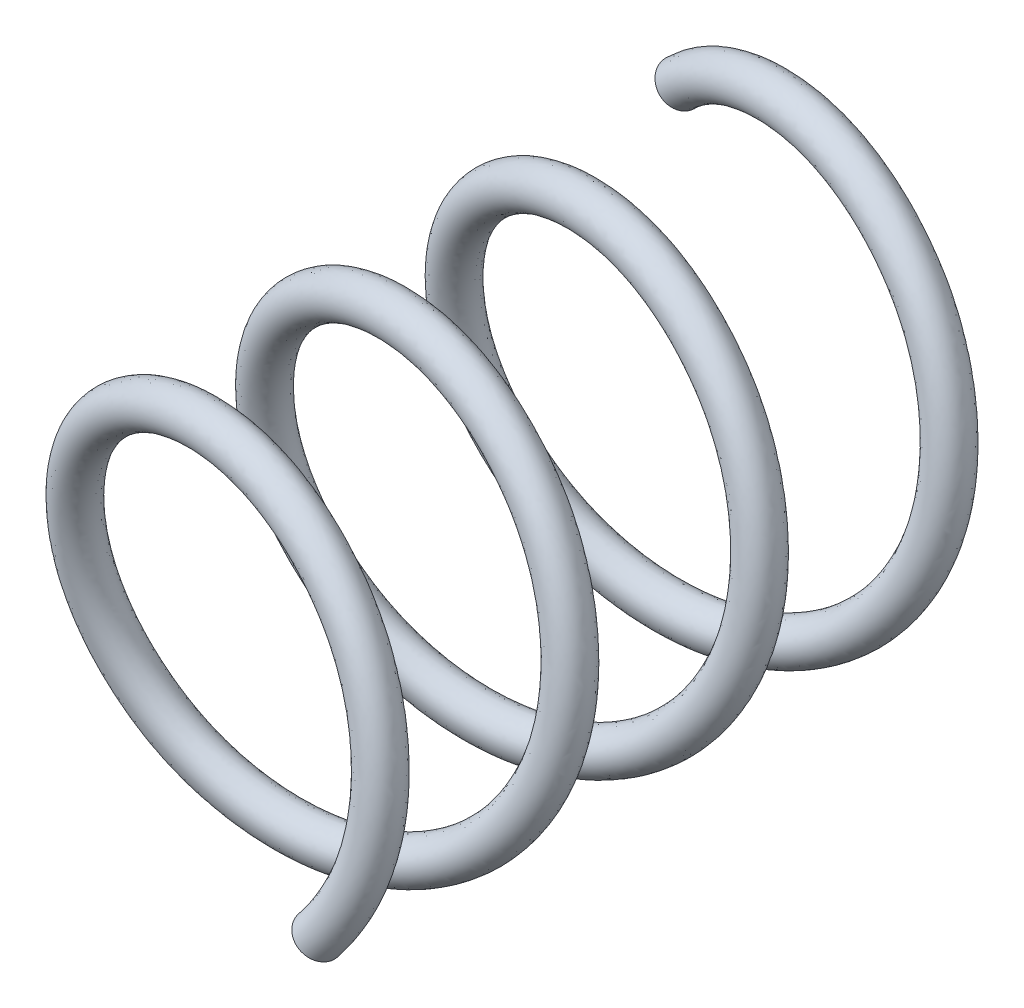
SolidWorks part; units mm, degrees
ref_plane "Płaszczyzna przednia" through (0, 0, 0) normal (0, 0, 1) x (1, 0, 0)
ref_plane "Płaszczyzna górna" through (0, 0, 0) normal (0, 1, 0) x (1, 0, 0)
ref_plane "Płaszczyzna prawa" through (0, 0, 0) normal (1, 0, 0) x (0, 0, -1)
sketch "Szkic1" plane through (0, 0, 0) normal (0, 0, 1) x (1, 0, 0)
  circle A0 centre (0, 0) radius 1.2
  dimension "D1" = 2.4
curve "Helisa/Spirala1" pitch 1.15 height 4 turns 3.4783
sketch "Szkic2" plane through (0, 0, 0) normal (1, 0, 0) x (0, 0, -1)
  circle A0 centre (-3.5938, 1.1999) radius 0.125
  point P2 (0, 0)
  point P3 (0, 0)
  dimension "D1" = 0.25
sweep "Wyciągnięcie po ścieżce1" add profiles "Szkic2" path "Helisa/Spirala1"
